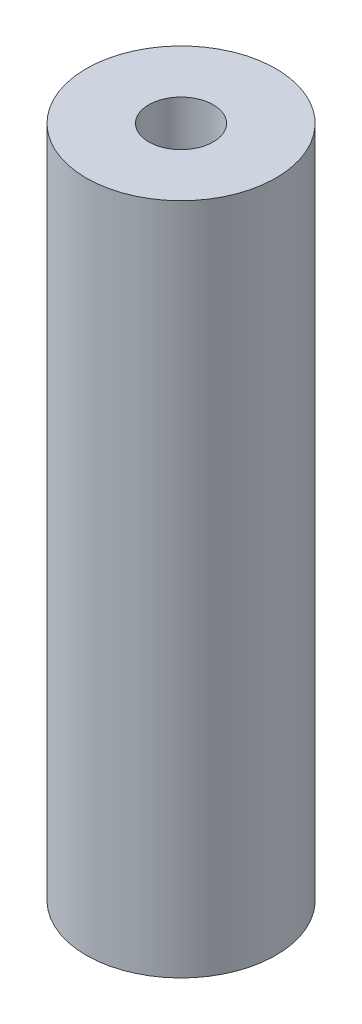
SolidWorks part; units mm, degrees
ref_plane "Front Plane" through (0, 0, 0) normal (0, 0, 1) x (1, 0, 0)
ref_plane "Top Plane" through (0, 0, 0) normal (0, 1, 0) x (1, 0, 0)
ref_plane "Right Plane" through (0, 0, 0) normal (1, 0, 0) x (0, 0, -1)
sketch "Sketch1" plane through (0, 0, 0) normal (0, 1, 0) x (1, 0, 0)
  circle A0 centre (0, 0) radius 5
  dimension "D1" = 10
extrude "Boss-Extrude1" add sketch "Sketch1" along normal blind 35.5
hole_wizard "M3 Clearance Hole1" positions "Sketch2" profile "Sketch3" hole size "M3" standard "ANSI Metric" end condition through all
sketch "Sketch2" plane through (0, 35.5, 0) normal (0, 1, 0) x (1, 0, 0)
  point P0 (0, 0)
sketch "Sketch3" plane through (0, 35.5, 0) normal (1, 0, 0) x (0, 0, 1)
  line L0 (0, 0) -> (0, 35.5)
  line L1 (0, 35.5) -> (1.7, 35.5)
  line L2 (1.7, 35.5) -> (1.7, 0)
  line L5 (1.7, 0) -> (0, 0)
  line L11 (0, -6.35) -> (0, 107.95) construction
  dimension "Thru Hole Dia." = 3.4
  dimension "Thru Hole Depth" = 35.5
